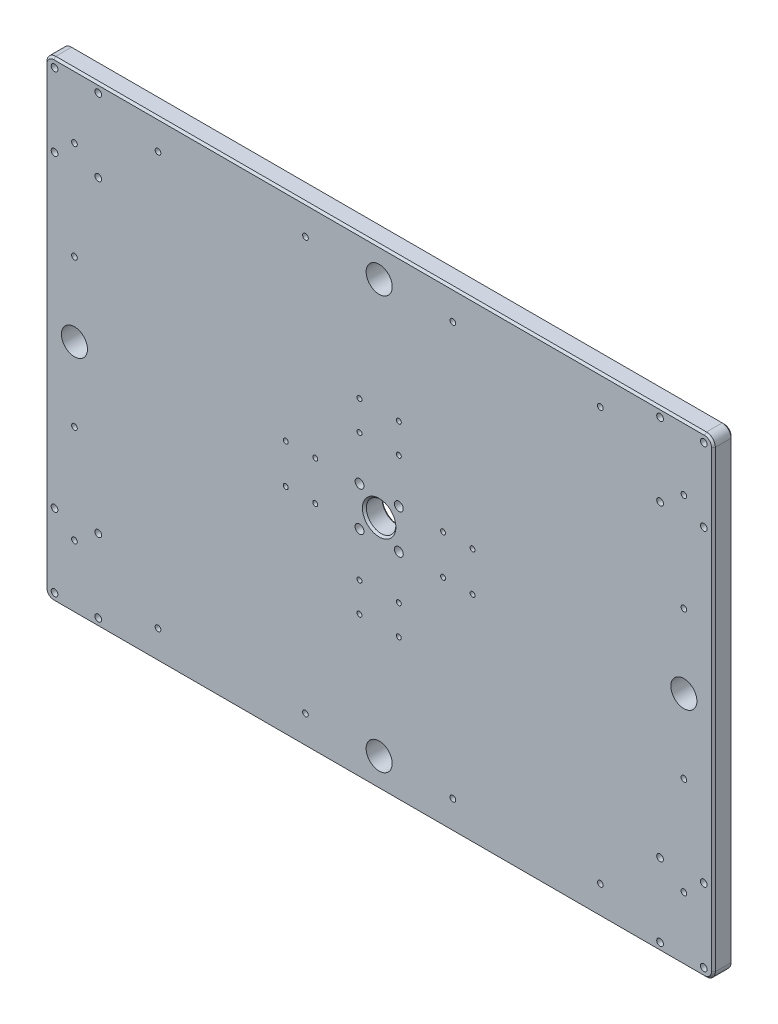
SolidWorks part; units mm, degrees
material "AL6061"
ref_plane "前视基准面" through (0, 0, 0) normal (0, 0, 1) x (1, 0, 0)
ref_plane "上视基准面" through (0, 0, 0) normal (0, 1, 0) x (1, 0, 0)
ref_plane "右视基准面" through (0, 0, 0) normal (1, 0, 0) x (0, 0, -1)
sketch "草图1" plane through (0, 0, 0) normal (0, 0, 1) x (1, 0, 0)
  line L1 (-340, 240) -> (340, 240)
  line L2 (-340, 240) -> (-340, -240)
  line L3 (-340, -240) -> (340, -240)
  line L4 (340, 240) -> (340, -240)
  line L5 (-340, 240) -> (340, -240) construction
  line L6 (-340, -240) -> (340, 240) construction
  point P0 (0, 0)
  dimension "D1" = 680
  dimension "D2" = 480
extrude "凸台-拉伸1" add sketch "草图1" along normal blind 20
fillet "圆角1" radius 9 4 edges at (-340, 240, 10) (340, 240, 10) (340, -240, 10) (-340, -240, 10)
chamfer "倒角3" distance 2 angle 45 16 edges at (-337.364, -237.364, 0) (0, -240, 0) (337.364, -237.364, 0) (340, 0, 0) (337.364, 237.364, 0) (0, 240, 0) (-337.364, 237.364, 0) (-340, 0, 0) (337.364, 237.364, 20) (340, 0, 20) (337.364, -237.364, 20) (0, -240, 20) (-337.364, -237.364, 20) (-340, 0, 20) (-337.364, 237.364, 20) (0, 240, 20)
hole_wizard "M30 螺纹孔1" positions "草图4" profile "草图5" tap size "M30" standard "GB"
sketch "草图4" plane through (0, 0, 0) normal (0, 0, -1) x (-1, 0, 0)
  line L1 (-310, 210) -> (310, 210) construction
  line L2 (-310, 210) -> (-310, -210) construction
  line L3 (-310, -210) -> (310, -210) construction
  line L4 (310, 210) -> (310, -210) construction
  line L5 (-310, 210) -> (310, -210) construction
  line L6 (-310, -210) -> (310, 210) construction
  line L7 (-331, 240) -> (331, 240) construction
  line L8 (-340, -231) -> (-340, 231) construction
  point P0 (0, 210)
  point P2 (-310, 0)
  point P4 (0, -210)
  point P6 (310, 0)
  point P101 (0, 0)
  dimension "D1" = 30
  dimension "D2" = 30
sketch "草图5" plane through (0, 210, 0) normal (1, 0, 0) x (0, 1, 0)
  line L0 (0, 0) -> (0, 78.4614)
  line L1 (0, 78.4614) -> (13.25, 70.5)
  line L2 (13.25, 70.5) -> (13.25, 0)
  line L5 (13.25, 0) -> (0, 0)
  line L10 (0, 78.4614) -> (-13.25, 70.5) construction
  line L11 (0, -6.35) -> (0, 107.95) construction
  dimension "螺纹孔钻头直径" = 26.5
  dimension "螺纹孔钻头深度" = 70.5
  dimension "导头角度" = 118
cosmetic thread "孔螺蚊线1" parameters "D1"=60, "D2"=30
cosmetic thread "孔螺蚊线2" parameters "D1"=60, "D2"=30
cosmetic thread "孔螺蚊线3" parameters "D1"=60, "D2"=30
cosmetic thread "孔螺蚊线4" parameters "D1"=60, "D2"=30
hole_wizard "打孔尺寸(%根据)内六角圆柱头螺钉的类型1" positions "草图6" profile "草图7" counterbore size "M8" standard "GB"
sketch "草图6" plane through (0, 0, 0) normal (0, 0, -1) x (-1, 0, 0)
  point P0 (20, -20)
  point P3 (-20, -20)
  point P6 (-20, 20)
  point P9 (20, 20)
sketch "草图7" plane through (-20, -20, 0) normal (1, 0, 0) x (0, 1, 0)
  line L0 (0, 0) -> (0, 73.2039)
  line L1 (0, 73.2039) -> (4.5, 70.5)
  line L2 (4.5, 70.5) -> (4.5, 9)
  line L3 (4.5, 9) -> (7.5, 9)
  line L4 (7.5, 9) -> (7.5, 0)
  line L5 (7.5, 0) -> (0, 0)
  line L10 (0, 73.2039) -> (-4.5, 70.5) construction
  line L11 (0, -6.35) -> (0, 107.95) construction
  dimension "孔直径" = 9
  dimension "孔深度" = 70.5
  dimension "柱形沉头孔直径" = 15
  dimension "柱形沉头孔深度" = 9
  dimension "导头角度" = 118
sketch "草图8" plane through (0, 0, 20) normal (0, 0, 1) x (1, 0, 0)
  circle A0 centre (0, 0) radius 15
  dimension "D1" = 30
extrude "切除-拉伸2" cut sketch "草图8" against normal through all
chamfer "倒角5" distance 2 angle 45 2 edges at (15, 0, 0) (15, 0, 20)
hole_wizard "M6 螺纹孔1" positions "草图9" profile "草图10" tap size "M6" standard "GB" end condition through all
sketch "草图9" plane through (0, 0, 20) normal (0, 0, 1) x (1, 0, 0)
  line L0 (23.3, 95) -> (16.7, 95) construction
  line L1 (23.3, 89) -> (23.3, 101) construction
  line L2 (16.7, 101) -> (16.7, 89) construction
  line L5 (23.3, 65) -> (16.7, 65) construction
  line L6 (23.3, 59) -> (23.3, 71) construction
  line L7 (16.7, 71) -> (16.7, 59) construction
  line L10 (-16.7, 95) -> (-23.3, 95) construction
  line L11 (-16.7, 89) -> (-16.7, 101) construction
  line L12 (-23.3, 101) -> (-23.3, 89) construction
  line L15 (-16.7, 65) -> (-23.3, 65) construction
  line L16 (-16.7, 59) -> (-16.7, 71) construction
  line L17 (-23.3, 71) -> (-23.3, 59) construction
  line L20 (23.3, -65) -> (16.7, -65) construction
  line L21 (23.3, -71) -> (23.3, -59) construction
  line L22 (16.7, -59) -> (16.7, -71) construction
  line L25 (23.3, -95) -> (16.7, -95) construction
  line L26 (23.3, -101) -> (23.3, -89) construction
  line L27 (16.7, -89) -> (16.7, -101) construction
  line L31 (-16.7, -65) -> (-23.3, -65) construction
  line L32 (-16.7, -71) -> (-16.7, -59) construction
  line L33 (-23.3, -59) -> (-23.3, -71) construction
  line L36 (-16.7, -95) -> (-23.3, -95) construction
  line L37 (-16.7, -101) -> (-16.7, -89) construction
  line L38 (-23.3, -89) -> (-23.3, -101) construction
  line L39 (65, 23.3) -> (65, 16.7) construction
  line L40 (71, 23.3) -> (59, 23.3) construction
  line L41 (59, 16.7) -> (71, 16.7) construction
  line L44 (65, -16.7) -> (65, -23.3) construction
  line L45 (71, -16.7) -> (59, -16.7) construction
  line L46 (59, -23.3) -> (71, -23.3) construction
  line L49 (95, -16.7) -> (95, -23.3) construction
  line L50 (101, -16.7) -> (89, -16.7) construction
  line L51 (89, -23.3) -> (101, -23.3) construction
  line L54 (95, 23.3) -> (95, 16.7) construction
  line L55 (101, 23.3) -> (89, 23.3) construction
  line L56 (89, 16.7) -> (101, 16.7) construction
  line L60 (-95, 23.3) -> (-95, 16.7) construction
  line L61 (-89, 23.3) -> (-101, 23.3) construction
  line L62 (-101, 16.7) -> (-89, 16.7) construction
  line L66 (-65, 23.3) -> (-65, 16.7) construction
  line L67 (-59, 23.3) -> (-71, 23.3) construction
  line L68 (-71, 16.7) -> (-59, 16.7) construction
  line L72 (-95, -16.7) -> (-95, -23.3) construction
  line L73 (-89, -16.7) -> (-101, -16.7) construction
  line L74 (-101, -23.3) -> (-89, -23.3) construction
  line L77 (-65, -16.7) -> (-65, -23.3) construction
  line L78 (-59, -16.7) -> (-71, -16.7) construction
  line L79 (-71, -23.3) -> (-59, -23.3) construction
  point P78 (20, 95)
  point P80 (20, 65)
  point P82 (-20, 65)
  point P84 (-20, 95)
  point P86 (20, -65)
  point P88 (20, -95)
  point P90 (-20, -95)
  point P92 (-20, -65)
  point P174 (-95, 20)
  point P176 (-65, 20)
  point P178 (-65, -20)
  point P180 (-95, -20)
  point P182 (65, 20)
  point P184 (95, 20)
  point P186 (95, -20)
  point P188 (65, -20)
sketch "草图10" plane through (65, -20, 20) normal (1, 0, 0) x (0, -1, 0)
  line L0 (0, 0) -> (0, 20)
  line L1 (0, 20) -> (2.5, 20)
  line L2 (2.5, 20) -> (2.5, 0)
  line L5 (2.5, 0) -> (0, 0)
  line L11 (0, -6.35) -> (0, 107.95) construction
  dimension "通孔螺纹孔钻头直径" = 5
  dimension "通孔螺纹孔钻头深度" = 20
cosmetic thread "孔螺蚊线5" parameters "D2"=6
cosmetic thread "孔螺蚊线6" parameters "D2"=6
cosmetic thread "孔螺蚊线7" parameters "D2"=6
cosmetic thread "孔螺蚊线8" parameters "D2"=6
cosmetic thread "孔螺蚊线9" parameters "D2"=6
cosmetic thread "孔螺蚊线10" parameters "D2"=6
cosmetic thread "孔螺蚊线11" parameters "D2"=6
cosmetic thread "孔螺蚊线12" parameters "D2"=6
cosmetic thread "孔螺蚊线13" parameters "D2"=6
cosmetic thread "孔螺蚊线14" parameters "D2"=6
cosmetic thread "孔螺蚊线15" parameters "D2"=6
cosmetic thread "孔螺蚊线16" parameters "D2"=6
cosmetic thread "孔螺蚊线17" parameters "D2"=6
cosmetic thread "孔螺蚊线18" parameters "D2"=6
cosmetic thread "孔螺蚊线19" parameters "D2"=6
cosmetic thread "孔螺蚊线20" parameters "D2"=6
sketch "草图16" plane through (0, 0, 0) normal (0, 0, -1) x (-1, 0, 0)
  line L1 (330.25, -231.25) -> (285.75, -231.25) construction
  line L2 (330.25, -231.25) -> (330.25, -156.75) construction
  line L3 (330.25, -156.75) -> (285.75, -156.75) construction
  line L4 (285.75, -231.25) -> (285.75, -156.75) construction
  line L5 (330.25, -231.25) -> (285.75, -156.75) construction
  line L6 (330.25, -156.75) -> (285.75, -231.25) construction
  line L7 (-330.25, -231.25) -> (-285.75, -231.25) construction
  line L8 (-330.25, -231.25) -> (-330.25, -156.75) construction
  line L9 (-330.25, -156.75) -> (-285.75, -156.75) construction
  line L10 (-285.75, -231.25) -> (-285.75, -156.75) construction
  line L11 (-330.25, -231.25) -> (-285.75, -156.75) construction
  line L12 (-330.25, -156.75) -> (-285.75, -231.25) construction
  line L13 (330.25, 231.25) -> (285.75, 231.25) construction
  line L14 (330.25, 231.25) -> (330.25, 156.75) construction
  line L15 (330.25, 156.75) -> (285.75, 156.75) construction
  line L16 (285.75, 231.25) -> (285.75, 156.75) construction
  line L17 (330.25, 231.25) -> (285.75, 156.75) construction
  line L18 (330.25, 156.75) -> (285.75, 231.25) construction
  line L19 (-330.25, 231.25) -> (-285.75, 231.25) construction
  line L20 (-330.25, 231.25) -> (-330.25, 156.75) construction
  line L21 (-330.25, 156.75) -> (-285.75, 156.75) construction
  line L22 (-285.75, 231.25) -> (-285.75, 156.75) construction
  line L23 (-330.25, 231.25) -> (-285.75, 156.75) construction
  line L24 (-330.25, 156.75) -> (-285.75, 231.25) construction
  circle A0 centre (308, 194) radius 27 construction
  circle A1 centre (-308, 194) radius 27 construction
  circle A2 centre (-308, -194) radius 27 construction
  circle A3 centre (308, -194) radius 27 construction
  circle A4 centre (308, 194) radius 27 construction
  circle A5 centre (-308, 194) radius 27 construction
  circle A6 centre (-308, -194) radius 27 construction
  circle A7 centre (308, -194) radius 27 construction
  dimension "D1" = 44.5
  dimension "D2" = 74.5
hole_wizard "M8 螺纹孔1" positions "草图17" profile "草图18" tap size "M8" standard "GB" end condition through all
sketch "草图17" plane through (0, 0, 0) normal (0, 0, -1) x (-1, 0, 0)
  line L0 (-285.75, -231.25) -> (-285.75, -156.75) construction
  point P0 (330.25, -231.25)
  point P3 (285.75, -231.25)
  point P6 (285.75, -156.75)
  point P9 (330.25, -156.75)
  point P12 (-285.75, -231.25)
  point P16 (-330.25, -231.25)
  point P19 (-330.25, -156.75)
  point P22 (-285.75, -156.75)
  point P28 (330.25, 156.75)
  point P31 (285.75, 156.75)
  point P34 (285.75, 231.25)
  point P37 (330.25, 231.25)
  point P40 (-285.75, 156.75)
  point P43 (-330.25, 156.75)
  point P46 (-330.25, 231.25)
  point P49 (-285.75, 231.25)
cosmetic thread "孔螺蚊线21" parameters "D2"=8
cosmetic thread "孔螺蚊线22" parameters "D2"=8
cosmetic thread "孔螺蚊线23" parameters "D2"=8
cosmetic thread "孔螺蚊线24" parameters "D2"=8
cosmetic thread "孔螺蚊线25" parameters "D2"=8
cosmetic thread "孔螺蚊线26" parameters "D2"=8
cosmetic thread "孔螺蚊线27" parameters "D2"=8
cosmetic thread "孔螺蚊线28" parameters "D2"=8
cosmetic thread "孔螺蚊线29" parameters "D2"=8
cosmetic thread "孔螺蚊线30" parameters "D2"=8
cosmetic thread "孔螺蚊线31" parameters "D2"=8
cosmetic thread "孔螺蚊线32" parameters "D2"=8
cosmetic thread "孔螺蚊线33" parameters "D2"=8
cosmetic thread "孔螺蚊线34" parameters "D2"=8
cosmetic thread "孔螺蚊线35" parameters "D2"=8
cosmetic thread "孔螺蚊线36" parameters "D2"=8
sketch "草图18" plane through (-330.25, -231.25, 0) normal (1, 0, 0) x (0, 1, 0)
  line L0 (0, 0) -> (0, 20)
  line L1 (0, 20) -> (3.4, 20)
  line L2 (3.4, 20) -> (3.4, 0)
  line L5 (3.4, 0) -> (0, 0)
  line L11 (0, -6.35) -> (0, 107.95) construction
  dimension "通孔螺纹孔钻头直径" = 6.8
  dimension "通孔螺纹孔钻头深度" = 20
hole_wizard "打孔尺寸(%根据)内六角圆柱头螺钉的类型2" positions "草图19" profile "草图20" counterbore size "M6" standard "GB"
sketch "草图19" plane through (0, 0, 0) normal (0, 0, -1) x (-1, 0, 0)
  line L0 (0, -240) -> (0, -210) construction
  line L1 (331, -240) -> (-331, -240) construction
  line L3 (75, -210) -> (-75, -210) construction
  line L5 (225, -210) -> (-225, -210) construction
  line L7 (0, 240) -> (0, 210) construction
  line L8 (-331, 240) -> (331, 240) construction
  line L10 (75, 210) -> (-75, 210) construction
  line L12 (225, 210) -> (-225, 210) construction
  line L14 (340, 0) -> (310, 0) construction
  line L15 (340, 231) -> (340, -231) construction
  line L17 (310, -75) -> (310, 75) construction
  line L19 (310, -175) -> (310, 175) construction
  line L20 (-340, 0) -> (-310, 0) construction
  line L21 (-340, -231) -> (-340, 231) construction
  line L23 (-310, -75) -> (-310, 75) construction
  line L25 (-310, -175) -> (-310, 175) construction
  point P0 (225, -210)
  point P2 (75, -210)
  point P4 (-75, -210)
  point P6 (-225, -210)
  point P8 (225, 210)
  point P10 (75, 210)
  point P12 (-75, 210)
  point P14 (-225, 210)
  point P17 (310, -175)
  point P19 (310, 175)
  point P21 (-310, -175)
  point P23 (-310, 175)
  point P35 (0, -210)
  point P43 (0, -210)
  point P55 (0, 210)
  point P61 (0, 210)
  point P77 (310, 0)
  point P82 (310, 0)
  point P95 (-310, 0)
  point P100 (-310, 0)
  point P105 (-310, -75)
  point P108 (-310, 75)
  point P112 (310, -75)
  point P115 (310, 75)
  dimension "D1" = 30
  dimension "D2" = 150
  dimension "D3" = 150
  dimension "D4" = 30
  dimension "D5" = 150
  dimension "D6" = 150
  dimension "D7" = 150
  dimension "D8" = 30
  dimension "D9" = 100
  dimension "D10" = 30
  dimension "D11" = 100
sketch "草图20" plane through (-225, -210, 0) normal (1, 0, 0) x (0, 1, 0)
  line L0 (0, 0) -> (0, 21.7328)
  line L1 (0, 21.7328) -> (3.3, 19.75)
  line L2 (3.3, 19.75) -> (3.3, 6.8)
  line L3 (3.3, 6.8) -> (5.5, 6.8)
  line L4 (5.5, 6.8) -> (5.5, 0)
  line L5 (5.5, 0) -> (0, 0)
  line L10 (0, 21.7328) -> (-3.3, 19.75) construction
  line L11 (0, -6.35) -> (0, 107.95) construction
  dimension "孔直径" = 6.6
  dimension "孔深度" = 19.75
  dimension "柱形沉头孔直径" = 11
  dimension "柱形沉头孔深度" = 6.8
  dimension "导头角度" = 118
